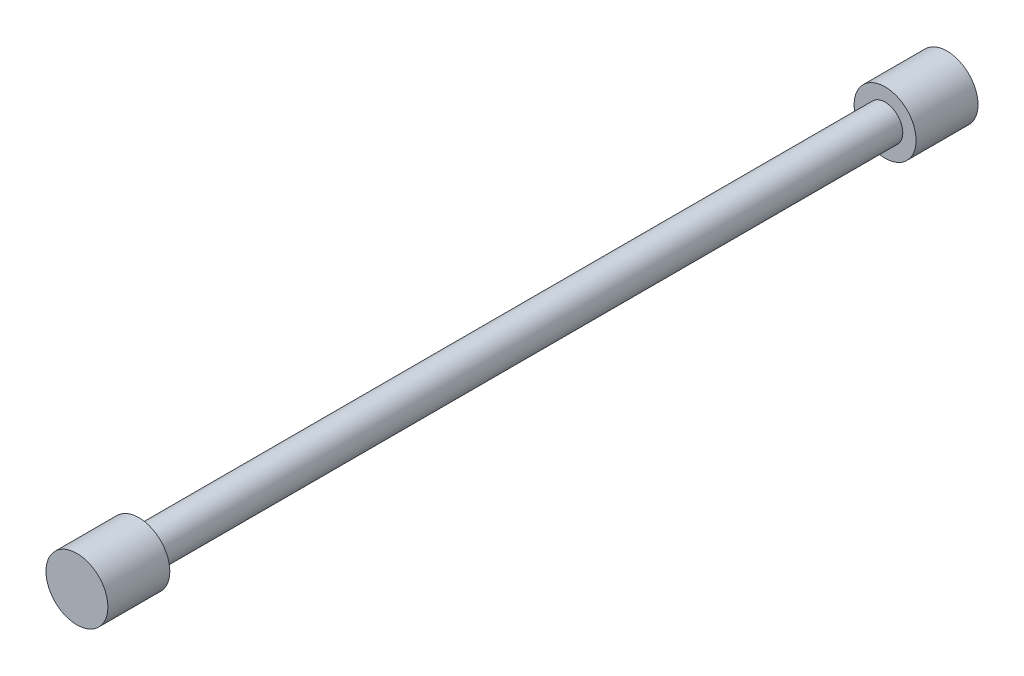
SolidWorks part; units mm, degrees
ref_plane "Front Plane" through (0, 0, 0) normal (0, 0, 1) x (1, 0, 0)
ref_plane "Top Plane" through (0, 0, 0) normal (0, 1, 0) x (1, 0, 0)
ref_plane "Right Plane" through (0, 0, 0) normal (1, 0, 0) x (0, 0, -1)
sketch "SK_Rod" plane through (0, 0, 0) normal (0, 1, 0) x (1, 0, 0)
  line L0 (0, -10) -> (0, 192.6691) construction
  line L1 (0, -7) -> (7, -7)
  line L2 (7, -7) -> (7, 7)
  line L3 (7, 7) -> (4, 7)
  line L4 (4, 7) -> (4, 175.6691)
  line L5 (4, 175.6691) -> (7, 175.6691)
  line L6 (7, 175.6691) -> (7, 189.6691)
  line L7 (7, 189.6691) -> (0, 189.6691)
  line L8 (0, 189.6691) -> (0, -7)
  dimension "P1" = 10
  dimension "P2" = 192.6691
  dimension "P3" = 7
  dimension "P4" = 7
  dimension "P5" = 7
  dimension "P6" = 7
  dimension "P7" = 7
  dimension "P8" = 4
  dimension "P9" = 7
  dimension "P10" = 4
  dimension "P11" = 175.6691
  dimension "P12" = 7
  dimension "P13" = 175.6691
  dimension "P14" = 7
  dimension "P15" = 189.6691
  dimension "P16" = 189.6691
revolve "Rod_Body" add sketch "SK_Rod" angle 360 about L0
sketch "SK_Ends" plane through (0, 0, 0) normal (0, 1, 0) x (1, 0, 0)
  point P0 (0, 0)
  point P2 (0, 182.6691)
  dimension "P1" = 182.6691
equation "\"Rod_length\" = 182.669"
